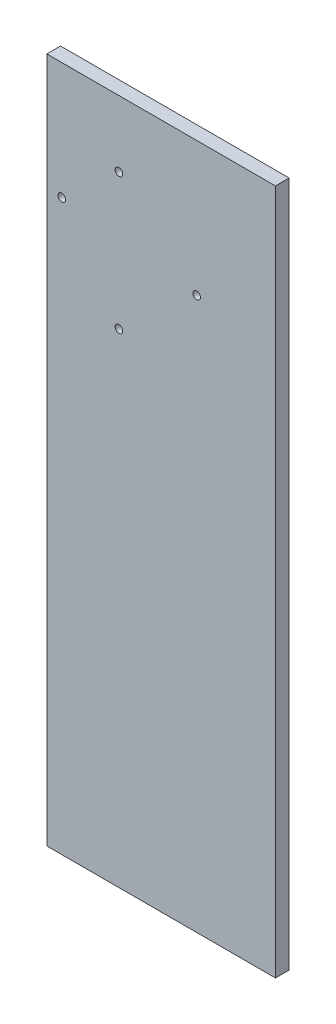
SolidWorks part; units mm, degrees
ref_plane "Front Plane" through (0, 0, 0) normal (0, 0, 1) x (1, 0, 0)
ref_plane "Top Plane" through (0, 0, 0) normal (0, 1, 0) x (1, 0, 0)
ref_plane "Right Plane" through (0, 0, 0) normal (1, 0, 0) x (0, 0, -1)
sketch "Sketch1" plane through (0, 0, 0) normal (0, 1, 0) x (1, 0, 0)
  line L1 (-75, 4.5) -> (75, 4.5)
  line L2 (-75, 4.5) -> (-75, -4.5)
  line L3 (-75, -4.5) -> (75, -4.5)
  line L4 (75, 4.5) -> (75, -4.5)
  line L5 (-75, 4.5) -> (75, -4.5) construction
  line L6 (-75, -4.5) -> (75, 4.5) construction
  point P0 (0, 0)
  dimension "D1" = 150
  dimension "D2" = 9
extrude "Boss-Extrude1" add sketch "Sketch1" along normal blind 450
sketch "Sketch2" plane through (0, 0, 4.5) normal (0, 0, 1) x (1, 0, 0)
  line L0 (-75, 450) -> (-75, 0) construction
  line L1 (-75, 450) -> (75, 450) construction
  circle A0 centre (-27.7, 406.6) radius 2.5
  circle A1 centre (-27.7, 317.4) radius 2.5
  circle A2 centre (23.3, 362) radius 2.5
  circle A3 centre (-65.2, 373.3) radius 2.5
  point P8 (0, 362)
  dimension "D5" = 5
  dimension "D6" = 5
  dimension "D7" = 5
  dimension "D8" = 5
  dimension "D1" = 75
  dimension "D2" = 88
  dimension "D3" = 27.7
  dimension "D4" = 43.4
  dimension "D9" = 89.2
  dimension "D10" = 51
  dimension "D11" = 88.5
  dimension "D12" = 11.3
  dimension "D13" = 47.3
  dimension "D14" = 88
extrude "Cut-Extrude1" cut sketch "Sketch2" against normal up to next and the other way through all
